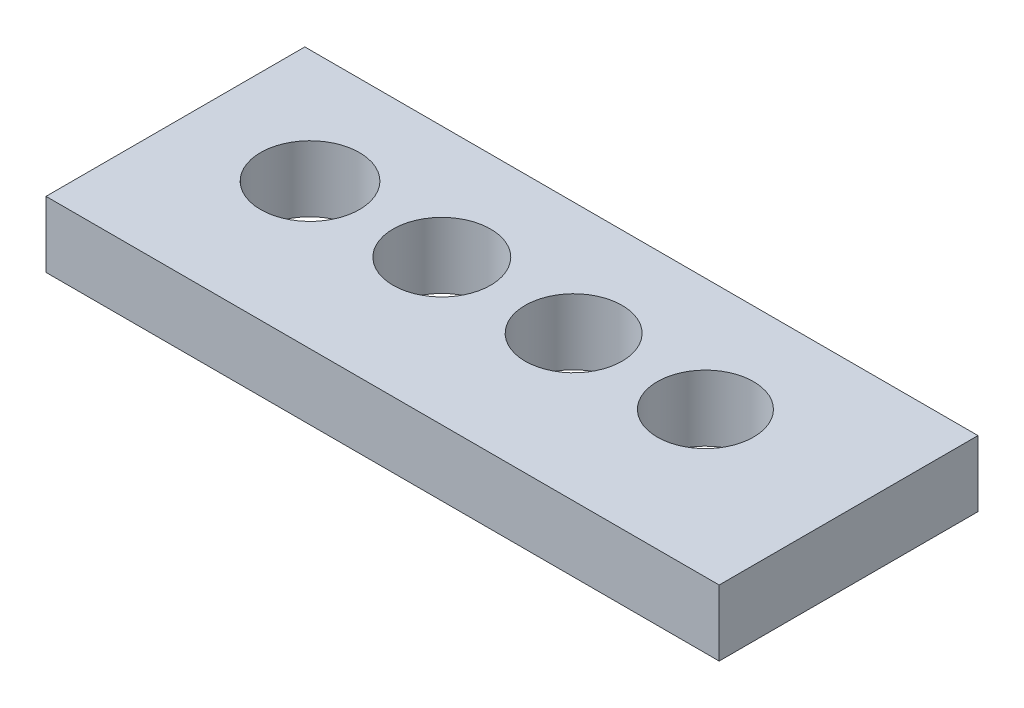
SolidWorks part; units mm, degrees
ref_plane "Front Plane" through (0, 0, 0) normal (0, 0, 1) x (1, 0, 0)
ref_plane "Top Plane" through (0, 0, 0) normal (0, 1, 0) x (1, 0, 0)
ref_plane "Right Plane" through (0, 0, 0) normal (1, 0, 0) x (0, 0, -1)
sketch "Sketch1" plane through (0, 0, 0) normal (0, 1, 0) x (1, 0, 0)
  line L1 (-18.0231, 17.2361) -> (84.1237, 17.2361)
  line L2 (-18.0231, 17.2361) -> (-18.0231, -22.0385)
  line L3 (-18.0231, -22.0385) -> (84.1237, -22.0385)
  line L4 (84.1237, 17.2361) -> (84.1237, -22.0385)
  circle A0 centre (0, 0) radius 7.5
  circle A1 centre (20, 0) radius 7.4
  circle A2 centre (40, 0) radius 7.35
  circle A3 centre (60, 0) radius 7.3
  dimension "D1" = 15
  dimension "D2" = 14.8
  dimension "D4" = 14.7
  dimension "D5" = 14.6
  dimension "D3" = 20
  dimension "D6" = 20
  dimension "D7" = 20
extrude "Boss-Extrude1" add sketch "Sketch1" along normal blind 10
